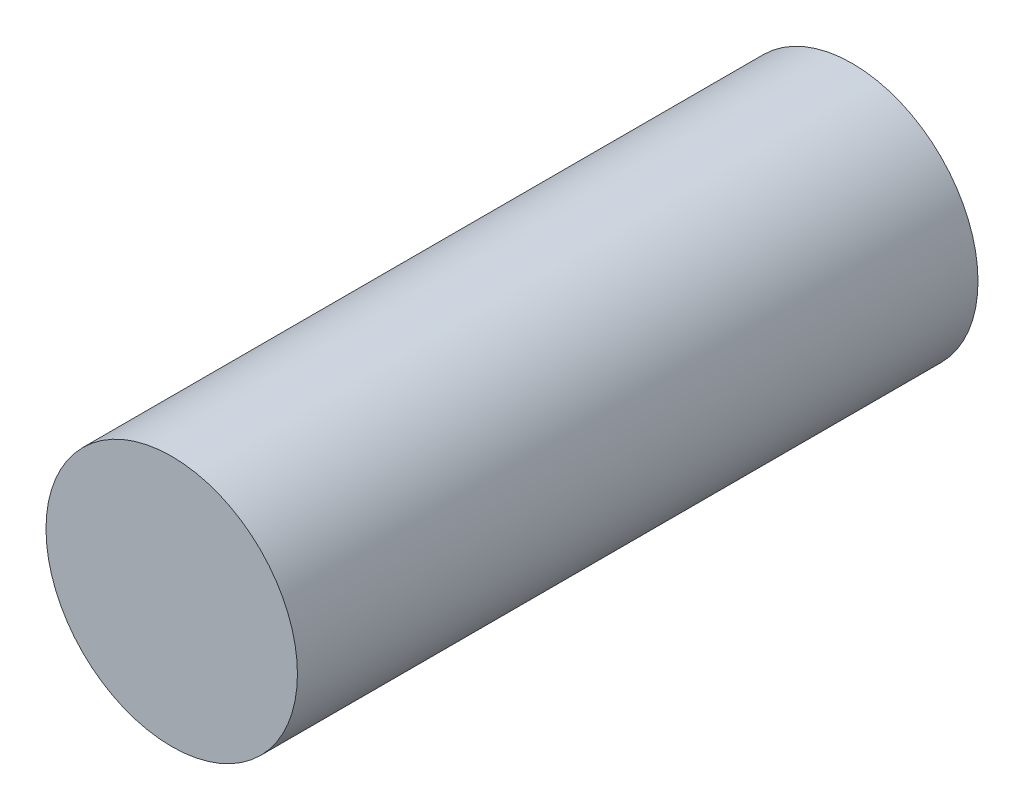
SolidWorks part; units mm, degrees
ref_plane "前视基准面" through (0, 0, 0) normal (0, 0, 1) x (1, 0, 0)
ref_plane "上视基准面" through (0, 0, 0) normal (0, 1, 0) x (1, 0, 0)
ref_plane "右视基准面" through (0, 0, 0) normal (1, 0, 0) x (0, 0, -1)
other "Configuration Table"
sketch "草图1" plane through (0, 0, 0) normal (0, 0, 1) x (1, 0, 0)
  circle A0 centre (0, 0) radius 0.75
extrude "凸台-拉伸1" add sketch "草图1" along normal blind 4.06
